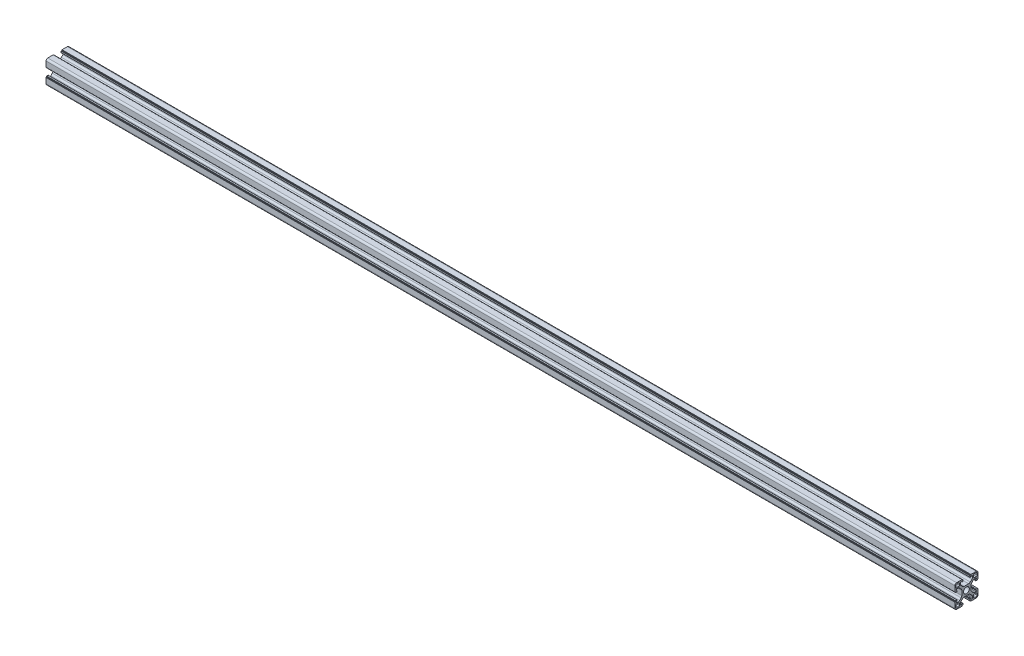
SolidWorks part; units mm, degrees
ref_plane "Спереди" through (0, 0, 0) normal (0, 0, 1) x (1, 0, 0)
ref_plane "Сверху" through (0, 0, 0) normal (0, 1, 0) x (1, 0, 0)
ref_plane "Справа" through (0, 0, 0) normal (1, 0, 0) x (0, 0, -1)
sketch "Эскиз1" plane through (0, 0, 0) normal (1, 0, 0) x (0, 0, -1)
  line L0 (9.2299, 9.7837) -> (6.2299, 6.7837) construction
  line L1 (0.1299, 4.6837) -> (2.0286, 4.6837)
  line L2 (0.1299, 0.6837) -> (10.1299, 10.6837) construction
  line L3 (7.7299, 8.2837) -> (6.2299, 9.7837) construction
  line L4 (3.4428, 5.2695) -> (4.7441, 6.5707)
  line L5 (7.0299, 6.7837) -> (8.4299, 6.7837)
  line L6 (6.2299, 7.5837) -> (6.2299, 8.9837)
  line L7 (8.4299, 9.7837) -> (7.0299, 9.7837)
  line L8 (5.3299, 8.8837) -> (5.3299, 7.9849)
  line L9 (3.8931, 8.757) -> (4.3734, 9.2373)
  line L10 (3.3299, 10.2328) -> (3.8299, 10.2328)
  line L11 (3.7163, 8.6837) -> (3.4299, 8.6837)
  line L12 (4.727, 9.3837) -> (4.8299, 9.3837)
  line L13 (3.8299, 10.5337) -> (3.8299, 10.2328)
  line L14 (3.1799, 10.0828) -> (3.1799, 8.9337)
  line L15 (8.6299, 10.6837) -> (3.9799, 10.6837)
  line L16 (9.2299, 8.9837) -> (9.2299, 7.5837)
  line L17 (10.1299, 9.1837) -> (10.1299, 4.5337)
  line L18 (9.5289, 3.7337) -> (8.3799, 3.7337)
  line L19 (9.9799, 4.3837) -> (9.6789, 4.3837)
  line L20 (8.8299, 5.2808) -> (8.8299, 5.3837)
  line L21 (8.1299, 4.2702) -> (8.1299, 3.9837)
  line L22 (9.6789, 3.8837) -> (9.6789, 4.3837)
  line L23 (8.2031, 4.447) -> (8.6834, 4.9273)
  line L24 (8.3299, 5.8837) -> (7.4311, 5.8837)
  line L25 (4.7156, 3.9967) -> (6.0169, 5.2979)
  line L26 (4.1299, 0.6837) -> (4.1299, 2.5825)
  line L27 (4.1299, 0.6837) -> (4.1299, -1.2151)
  line L28 (4.7156, -2.6293) -> (6.0169, -3.9305)
  line L29 (6.2299, -6.2163) -> (6.2299, -7.6163)
  line L30 (7.0299, -5.4163) -> (8.4299, -5.4163)
  line L31 (9.2299, -7.6163) -> (9.2299, -6.2163)
  line L32 (8.3299, -4.5163) -> (7.4311, -4.5163)
  line L33 (8.2031, -3.0795) -> (8.6834, -3.5598)
  line L34 (9.6789, -2.5163) -> (9.6789, -3.0163)
  line L35 (8.1299, -2.9027) -> (8.1299, -2.6163)
  line L36 (8.8299, -3.9134) -> (8.8299, -4.0163)
  line L37 (9.9799, -3.0163) -> (9.6789, -3.0163)
  line L38 (9.5289, -2.3663) -> (8.3799, -2.3663)
  line L39 (10.1299, -7.8163) -> (10.1299, -3.1663)
  line L40 (8.4299, -8.4163) -> (7.0299, -8.4163)
  line L41 (8.6299, -9.3163) -> (3.9799, -9.3163)
  line L42 (3.1799, -8.7153) -> (3.1799, -7.5663)
  line L43 (3.8299, -9.1663) -> (3.8299, -8.8653)
  line L44 (4.727, -8.0163) -> (4.8299, -8.0163)
  line L45 (3.7163, -7.3163) -> (3.4299, -7.3163)
  line L46 (3.3299, -8.8653) -> (3.8299, -8.8653)
  line L47 (3.8931, -7.3895) -> (4.3734, -7.8698)
  line L48 (5.3299, -7.5163) -> (5.3299, -6.6175)
  line L49 (3.4428, -3.9021) -> (4.7441, -5.2033)
  line L50 (0.1299, -3.3163) -> (2.0286, -3.3163)
  line L51 (9.2299, -8.4163) -> (6.2299, -5.4163) construction
  line L52 (0.1299, 0.6837) -> (10.1299, -9.3163) construction
  line L53 (7.7299, -6.9163) -> (9.2299, -5.4163) construction
  line L54 (0.1299, -3.3163) -> (-1.7689, -3.3163)
  line L55 (-3.1831, -3.9021) -> (-4.4844, -5.2033)
  line L56 (-6.7701, -5.4163) -> (-8.1701, -5.4163)
  line L57 (-5.9701, -6.2163) -> (-5.9701, -7.6163)
  line L58 (-8.1701, -8.4163) -> (-6.7701, -8.4163)
  line L59 (-5.0701, -7.5163) -> (-5.0701, -6.6175)
  line L60 (-3.6334, -7.3895) -> (-4.1137, -7.8698)
  line L61 (-3.0701, -8.8653) -> (-3.5701, -8.8653)
  line L62 (-3.4566, -7.3163) -> (-3.1701, -7.3163)
  line L63 (-4.4673, -8.0163) -> (-4.5701, -8.0163)
  line L64 (-3.5701, -9.1663) -> (-3.5701, -8.8653)
  line L65 (-2.9201, -8.7153) -> (-2.9201, -7.5663)
  line L66 (-8.3701, -9.3163) -> (-3.7201, -9.3163)
  line L67 (-8.9701, -7.6163) -> (-8.9701, -6.2163)
  line L68 (-9.8701, -7.8163) -> (-9.8701, -3.1663)
  line L69 (-9.2692, -2.3663) -> (-8.1201, -2.3663)
  line L70 (-9.7201, -3.0163) -> (-9.4192, -3.0163)
  line L71 (-8.5701, -3.9134) -> (-8.5701, -4.0163)
  line L72 (-7.8701, -2.9027) -> (-7.8701, -2.6163)
  line L73 (-9.4192, -2.5163) -> (-9.4192, -3.0163)
  line L74 (-7.9434, -3.0795) -> (-8.4237, -3.5598)
  line L75 (-8.0701, -4.5163) -> (-7.1714, -4.5163)
  line L76 (-4.4559, -2.6293) -> (-5.7572, -3.9305)
  line L77 (-3.8701, 0.6837) -> (-3.8701, -1.2151)
  line L78 (-8.9701, -8.4163) -> (-5.9701, -5.4163) construction
  line L79 (0.1299, 0.6837) -> (-9.8701, -9.3163) construction
  line L80 (-7.4701, -6.9163) -> (-5.9701, -8.4163) construction
  line L81 (-3.8701, 0.6837) -> (-3.8701, 2.5825)
  line L82 (-4.4559, 3.9967) -> (-5.7572, 5.2979)
  line L83 (-5.9701, 7.5837) -> (-5.9701, 8.9837)
  line L84 (-6.7701, 6.7837) -> (-8.1701, 6.7837)
  line L85 (-8.9701, 8.9837) -> (-8.9701, 7.5837)
  line L86 (-8.0701, 5.8837) -> (-7.1714, 5.8837)
  line L87 (-7.9434, 4.447) -> (-8.4237, 4.9273)
  line L88 (-9.4192, 3.8837) -> (-9.4192, 4.3837)
  line L89 (-7.8701, 4.2702) -> (-7.8701, 3.9837)
  line L90 (-8.5701, 5.2808) -> (-8.5701, 5.3837)
  line L91 (-9.7201, 4.3837) -> (-9.4192, 4.3837)
  line L92 (-9.2692, 3.7337) -> (-8.1201, 3.7337)
  line L93 (-9.8701, 9.1837) -> (-9.8701, 4.5337)
  line L94 (-8.1701, 9.7837) -> (-6.7701, 9.7837)
  line L95 (-8.3701, 10.6837) -> (-3.7201, 10.6837)
  line L96 (-2.9201, 10.0828) -> (-2.9201, 8.9337)
  line L97 (-3.5701, 10.5337) -> (-3.5701, 10.2328)
  line L98 (-4.4673, 9.3837) -> (-4.5701, 9.3837)
  line L99 (-3.4566, 8.6837) -> (-3.1701, 8.6837)
  line L100 (-3.0701, 10.2328) -> (-3.5701, 10.2328)
  line L101 (-3.6334, 8.757) -> (-4.1137, 9.2373)
  line L102 (-5.0701, 8.8837) -> (-5.0701, 7.9849)
  line L103 (-3.1831, 5.2695) -> (-4.4844, 6.5707)
  line L104 (0.1299, 4.6837) -> (-1.7689, 4.6837)
  line L105 (-11.6342, 0.6837) -> (11.6342, 0.6837) construction
  line L106 (-8.9701, 9.7837) -> (-5.9701, 6.7837) construction
  line L107 (0.1299, -11.4027) -> (0.1299, 11.4027) construction
  line L108 (0.1299, 0.6837) -> (-9.8701, 10.6837) construction
  line L109 (-7.4701, 8.2837) -> (-8.9701, 6.7837) construction
  arc A0 (9.2299, 8.9837) -> (8.4299, 9.7837) centre (8.4299, 8.9837) ccw
  arc A1 (7.0299, 9.7837) -> (6.2299, 8.9837) centre (7.0299, 8.9837) ccw
  arc A2 (7.0299, 6.7837) -> (6.2299, 7.5837) centre (7.0299, 7.5837) cw
  arc A3 (8.6299, 10.6837) -> (10.1299, 9.1837) centre (8.6299, 9.1837) cw
  arc A4 (3.3299, 10.2328) -> (3.1799, 10.0828) centre (3.3299, 10.0828) ccw
  arc A5 (3.9799, 10.6837) -> (3.8299, 10.5337) centre (3.9799, 10.5337) ccw
  arc A6 (3.7163, 8.6837) -> (3.8931, 8.757) centre (3.7163, 8.9337) ccw
  arc A7 (3.4299, 8.6837) -> (3.1799, 8.9337) centre (3.4299, 8.9337) cw
  arc A8 (4.3734, 9.2373) -> (4.727, 9.3837) centre (4.727, 8.8837) cw
  arc A9 (4.8299, 9.3837) -> (5.3299, 8.8837) centre (4.8299, 8.8837) cw
  arc A10 (2.6299, 0.6837) -> (0.1299, 3.1837) centre (0.1299, 0.6837) ccw
  arc A11 (2.0286, 4.6837) -> (3.4428, 5.2695) centre (2.0286, 6.6837) ccw
  arc A12 (5.3299, 7.9849) -> (4.7441, 6.5707) centre (3.3299, 7.9849) cw
  arc A13 (9.2299, 7.5837) -> (8.4299, 6.7837) centre (8.4299, 7.5837) cw
  arc A14 (8.8299, 5.3837) -> (8.3299, 5.8837) centre (8.3299, 5.3837) ccw
  arc A15 (8.6834, 4.9273) -> (8.8299, 5.2808) centre (8.3299, 5.2808) ccw
  arc A16 (8.1299, 3.9837) -> (8.3799, 3.7337) centre (8.3799, 3.9837) ccw
  arc A17 (8.1299, 4.2702) -> (8.2031, 4.447) centre (8.3799, 4.2702) cw
  arc A18 (10.1299, 4.5337) -> (9.9799, 4.3837) centre (9.9799, 4.5337) cw
  arc A19 (9.6789, 3.8837) -> (9.5289, 3.7337) centre (9.5289, 3.8837) cw
  arc A20 (7.4311, 5.8837) -> (6.0169, 5.2979) centre (7.4311, 3.8837) ccw
  arc A21 (4.1299, 2.5825) -> (4.7156, 3.9967) centre (6.1299, 2.5825) cw
  arc A22 (8.4299, -8.4163) -> (9.2299, -7.6163) centre (8.4299, -7.6163) ccw
  arc A23 (9.2299, -6.2163) -> (8.4299, -5.4163) centre (8.4299, -6.2163) ccw
  arc A24 (6.2299, -6.2163) -> (7.0299, -5.4163) centre (7.0299, -6.2163) cw
  arc A25 (10.1299, -7.8163) -> (8.6299, -9.3163) centre (8.6299, -7.8163) cw
  arc A26 (9.6789, -2.5163) -> (9.5289, -2.3663) centre (9.5289, -2.5163) ccw
  arc A27 (10.1299, -3.1663) -> (9.9799, -3.0163) centre (9.9799, -3.1663) ccw
  arc A28 (8.1299, -2.9027) -> (8.2031, -3.0795) centre (8.3799, -2.9027) ccw
  arc A29 (8.1299, -2.6163) -> (8.3799, -2.3663) centre (8.3799, -2.6163) cw
  arc A30 (8.6834, -3.5598) -> (8.8299, -3.9134) centre (8.3299, -3.9134) cw
  arc A31 (8.8299, -4.0163) -> (8.3299, -4.5163) centre (8.3299, -4.0163) cw
  arc A32 (0.1299, -1.8163) -> (2.6299, 0.6837) centre (0.1299, 0.6837) ccw
  arc A33 (4.1299, -1.2151) -> (4.7156, -2.6293) centre (6.1299, -1.2151) ccw
  arc A34 (7.4311, -4.5163) -> (6.0169, -3.9305) centre (7.4311, -2.5163) cw
  arc A35 (7.0299, -8.4163) -> (6.2299, -7.6163) centre (7.0299, -7.6163) cw
  arc A36 (4.8299, -8.0163) -> (5.3299, -7.5163) centre (4.8299, -7.5163) ccw
  arc A37 (4.3734, -7.8698) -> (4.727, -8.0163) centre (4.727, -7.5163) ccw
  arc A38 (3.4299, -7.3163) -> (3.1799, -7.5663) centre (3.4299, -7.5663) ccw
  arc A39 (3.7163, -7.3163) -> (3.8931, -7.3895) centre (3.7163, -7.5663) cw
  arc A40 (3.9799, -9.3163) -> (3.8299, -9.1663) centre (3.9799, -9.1663) cw
  arc A41 (3.3299, -8.8653) -> (3.1799, -8.7153) centre (3.3299, -8.7153) cw
  arc A42 (5.3299, -6.6175) -> (4.7441, -5.2033) centre (3.3299, -6.6175) ccw
  arc A43 (2.0286, -3.3163) -> (3.4428, -3.9021) centre (2.0286, -5.3163) cw
  arc A44 (-8.9701, -7.6163) -> (-8.1701, -8.4163) centre (-8.1701, -7.6163) ccw
  arc A45 (-6.7701, -8.4163) -> (-5.9701, -7.6163) centre (-6.7701, -7.6163) ccw
  arc A46 (-6.7701, -5.4163) -> (-5.9701, -6.2163) centre (-6.7701, -6.2163) cw
  arc A47 (-8.3701, -9.3163) -> (-9.8701, -7.8163) centre (-8.3701, -7.8163) cw
  arc A48 (-3.0701, -8.8653) -> (-2.9201, -8.7153) centre (-3.0701, -8.7153) ccw
  arc A49 (-3.7201, -9.3163) -> (-3.5701, -9.1663) centre (-3.7201, -9.1663) ccw
  arc A50 (-3.4566, -7.3163) -> (-3.6334, -7.3895) centre (-3.4566, -7.5663) ccw
  arc A51 (-3.1701, -7.3163) -> (-2.9201, -7.5663) centre (-3.1701, -7.5663) cw
  arc A52 (-4.1137, -7.8698) -> (-4.4673, -8.0163) centre (-4.4673, -7.5163) cw
  arc A53 (-4.5701, -8.0163) -> (-5.0701, -7.5163) centre (-4.5701, -7.5163) cw
  arc A54 (-2.3701, 0.6837) -> (0.1299, -1.8163) centre (0.1299, 0.6837) ccw
  arc A55 (-1.7689, -3.3163) -> (-3.1831, -3.9021) centre (-1.7689, -5.3163) ccw
  arc A56 (-5.0701, -6.6175) -> (-4.4844, -5.2033) centre (-3.0701, -6.6175) cw
  arc A57 (-8.9701, -6.2163) -> (-8.1701, -5.4163) centre (-8.1701, -6.2163) cw
  arc A58 (-8.5701, -4.0163) -> (-8.0701, -4.5163) centre (-8.0701, -4.0163) ccw
  arc A59 (-8.4237, -3.5598) -> (-8.5701, -3.9134) centre (-8.0701, -3.9134) ccw
  arc A60 (-7.8701, -2.6163) -> (-8.1201, -2.3663) centre (-8.1201, -2.6163) ccw
  arc A61 (-7.8701, -2.9027) -> (-7.9434, -3.0795) centre (-8.1201, -2.9027) cw
  arc A62 (-9.8701, -3.1663) -> (-9.7201, -3.0163) centre (-9.7201, -3.1663) cw
  arc A63 (-9.4192, -2.5163) -> (-9.2692, -2.3663) centre (-9.2692, -2.5163) cw
  arc A64 (-7.1714, -4.5163) -> (-5.7572, -3.9305) centre (-7.1714, -2.5163) ccw
  arc A65 (-3.8701, -1.2151) -> (-4.4559, -2.6293) centre (-5.8701, -1.2151) cw
  arc A66 (-8.1701, 9.7837) -> (-8.9701, 8.9837) centre (-8.1701, 8.9837) ccw
  arc A67 (-8.9701, 7.5837) -> (-8.1701, 6.7837) centre (-8.1701, 7.5837) ccw
  arc A68 (-5.9701, 7.5837) -> (-6.7701, 6.7837) centre (-6.7701, 7.5837) cw
  arc A69 (-9.8701, 9.1837) -> (-8.3701, 10.6837) centre (-8.3701, 9.1837) cw
  arc A70 (-9.4192, 3.8837) -> (-9.2692, 3.7337) centre (-9.2692, 3.8837) ccw
  arc A71 (-9.8701, 4.5337) -> (-9.7201, 4.3837) centre (-9.7201, 4.5337) ccw
  arc A72 (-7.8701, 4.2702) -> (-7.9434, 4.447) centre (-8.1201, 4.2702) ccw
  arc A73 (-7.8701, 3.9837) -> (-8.1201, 3.7337) centre (-8.1201, 3.9837) cw
  arc A74 (-8.4237, 4.9273) -> (-8.5701, 5.2808) centre (-8.0701, 5.2808) cw
  arc A75 (-8.5701, 5.3837) -> (-8.0701, 5.8837) centre (-8.0701, 5.3837) cw
  arc A76 (0.1299, 3.1837) -> (-2.3701, 0.6837) centre (0.1299, 0.6837) ccw
  arc A77 (-3.8701, 2.5825) -> (-4.4559, 3.9967) centre (-5.8701, 2.5825) ccw
  arc A78 (-7.1714, 5.8837) -> (-5.7572, 5.2979) centre (-7.1714, 3.8837) cw
  arc A79 (-6.7701, 9.7837) -> (-5.9701, 8.9837) centre (-6.7701, 8.9837) cw
  arc A80 (-4.5701, 9.3837) -> (-5.0701, 8.8837) centre (-4.5701, 8.8837) ccw
  arc A81 (-4.1137, 9.2373) -> (-4.4673, 9.3837) centre (-4.4673, 8.8837) ccw
  arc A82 (-3.1701, 8.6837) -> (-2.9201, 8.9337) centre (-3.1701, 8.9337) ccw
  arc A83 (-3.4566, 8.6837) -> (-3.6334, 8.757) centre (-3.4566, 8.9337) cw
  arc A84 (-3.7201, 10.6837) -> (-3.5701, 10.5337) centre (-3.7201, 10.5337) cw
  arc A85 (-3.0701, 10.2328) -> (-2.9201, 10.0828) centre (-3.0701, 10.0828) cw
  arc A86 (-5.0701, 7.9849) -> (-4.4844, 6.5707) centre (-3.0701, 7.9849) ccw
  arc A87 (-1.7689, 4.6837) -> (-3.1831, 5.2695) centre (-1.7689, 6.6837) cw
  point P0 (0.1299, 0.6837)
  point P9 (0.1299, 0.6837)
  point P40 (8.8299, 4.3837)
  point P93 (3.8299, -8.0163)
  point P144 (3.8299, 9.3837)
  point P152 (8.8299, -3.0163)
  point P153 (0.1299, -3.2405)
  point P154 (0.1299, 0.6837)
  point P189 (-8.5701, -3.0163)
  point P228 (-3.5701, -8.0163)
  point P229 (-3.7944, 0.6837)
  point P230 (0.1299, 0.6837)
  point P268 (-3.5701, 9.3837)
  point P273 (4.0541, 0.6837)
  point P306 (-8.5701, 4.3837)
  point P307 (0.1299, 4.608)
  point P309 (0.1299, 0.6837)
  dimension "D5" = 2
  dimension "D1" = 2
  dimension "D2" = 6
  dimension "D3" = 4
  dimension "D4" = 0.9
extrude "Бобышка-Вытянуть1" add sketch "Эскиз1" along normal blind 785
